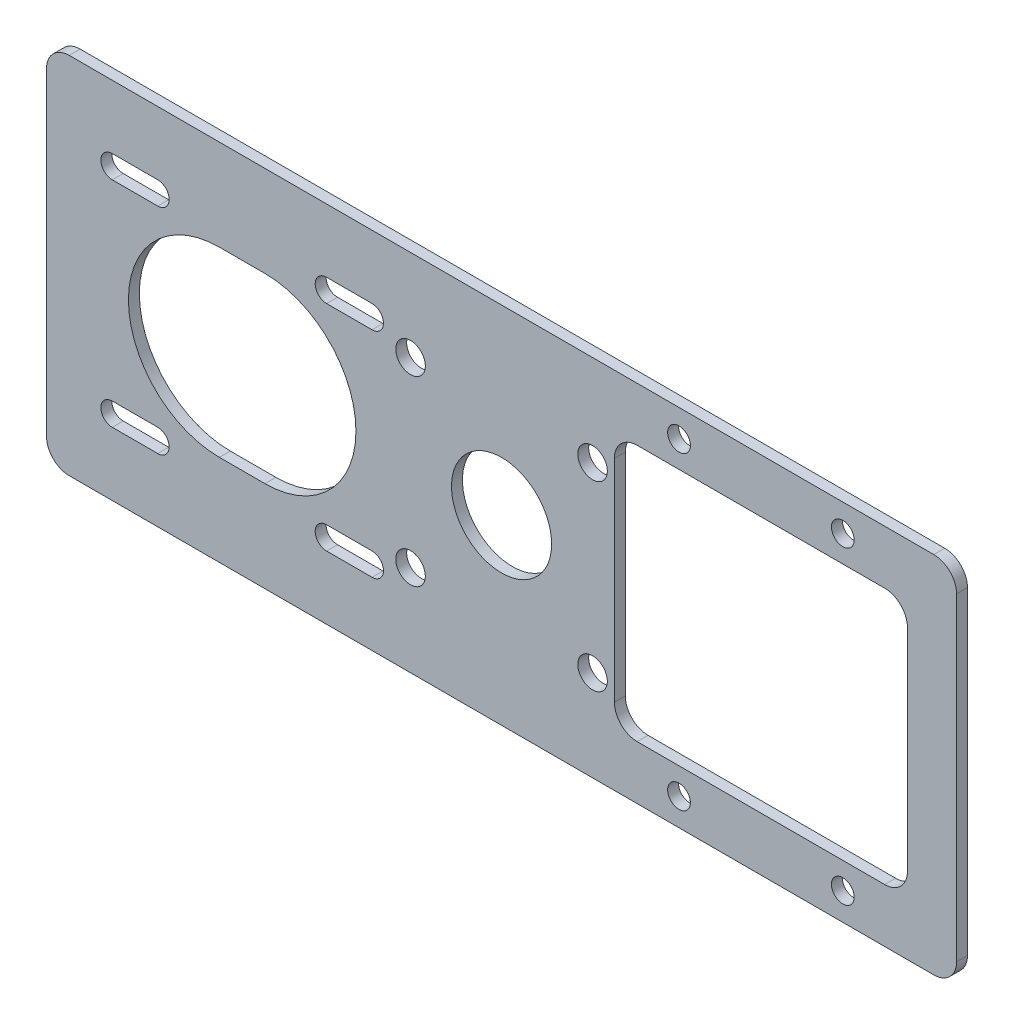
SolidWorks part; units mm, degrees
ref_plane "Alzado" through (0, 0, 0) normal (0, 0, 1) x (1, 0, 0)
ref_plane "Planta" through (0, 0, 0) normal (0, 1, 0) x (1, 0, 0)
ref_plane "Vista lateral" through (0, 0, 0) normal (1, 0, 0) x (0, 0, -1)
sketch "Croquis1" plane through (0, 0, 0) normal (0, 0, 1) x (1, 0, 0)
  line L1 (-100, 40) -> (100, 40)
  line L2 (-100, 40) -> (-100, -40)
  line L3 (-100, -40) -> (100, -40)
  line L4 (100, 40) -> (100, -40)
  line L5 (-100, 40) -> (100, -40) construction
  line L6 (-100, -40) -> (100, 40) construction
  point P0 (0, 0)
  dimension "D1" = 200
  dimension "D2" = 80
extrude "Saliente-Extruir1" add sketch "Croquis1" along normal blind 2.4
sketch "Croquis2" plane through (0, 0, 2.4) normal (0, 0, 1) x (1, 0, 0)
  circle A0 centre (0, 0) radius 11
  dimension "D1" = 22
extrude "Cortar-Extruir1" cut sketch "Croquis2" against normal through all
sketch "Croquis3" plane through (0, 0, 2.4) normal (0, 0, 1) x (1, 0, 0)
  line L0 (-20, 20) -> (-20, -20) construction
  line L1 (-27, 27) -> (27, 27) construction
  line L2 (-27, 27) -> (-27, -27) construction
  line L3 (-27, -27) -> (27, -27) construction
  line L4 (27, 27) -> (27, -27) construction
  line L5 (-27, 27) -> (27, -27) construction
  line L6 (-27, -27) -> (27, 27) construction
  line L7 (-20, -20) -> (20, -20) construction
  line L8 (20, 20) -> (20, -20) construction
  line L9 (-20, 20) -> (20, 20) construction
  circle A0 centre (20, 20) radius 3.25
  circle A1 centre (-20, 20) radius 3.25
  circle A2 centre (-20, -20) radius 3.25
  circle A3 centre (20, -20) radius 3.25
  point P0 (0, 0)
  dimension "D4" = 6.5
  dimension "D5" = 6.5
  dimension "D6" = 6.5
  dimension "D7" = 6.5
  dimension "D1" = 54
  dimension "D2" = 54
  dimension "D3" = 7
extrude "Cortar-Extruir2" cut sketch "Croquis3" against normal through all
sketch "Croquis4" plane through (0, 0, 2.4) normal (0, 0, 1) x (1, 0, 0)
  line L0 (0, 0) -> (-100, 0) construction
  line L1 (-100, 40) -> (-100, -40) construction
  line L2 (-57, 40) -> (-57, -40) construction
  line L3 (100, 40) -> (-100, 40) construction
  line L4 (-100, -40) -> (100, -40) construction
  line L5 (-62, 0) -> (-52, 0) construction
  line L6 (-85.2, 28.2) -> (-28.8, 28.2) construction
  line L7 (-85.2, 28.2) -> (-85.2, -28.2) construction
  line L8 (-85.2, -28.2) -> (-28.8, -28.2) construction
  line L9 (-28.8, 28.2) -> (-28.8, -28.2) construction
  line L10 (-85.2, 28.2) -> (-28.8, -28.2) construction
  line L11 (-85.2, -28.2) -> (-28.8, 28.2) construction
  line L12 (-27, 27) -> (27, 27) construction
  line L13 (-27, 27) -> (-27, -27) construction
  line L14 (-27, -27) -> (27, -27) construction
  line L15 (27, 27) -> (27, -27) construction
  line L16 (-27, 27) -> (27, -27) construction
  line L17 (-27, -27) -> (27, 27) construction
  line L18 (-62, 20) -> (-52, 20)
  line L19 (-62, -20) -> (-52, -20)
  line L20 (-85.55, 23.55) -> (-75.55, 23.55) construction
  line L21 (-33.45, -23.55) -> (-80.55, -23.55) construction
  line L22 (-33.45, -23.55) -> (-33.45, 23.55) construction
  line L23 (-33.45, 23.55) -> (-80.55, 23.55) construction
  line L24 (-80.55, -23.55) -> (-80.55, 23.55) construction
  line L25 (-33.45, -23.55) -> (-80.55, 23.55) construction
  line L26 (-33.45, 23.55) -> (-80.55, -23.55) construction
  line L27 (-85.55, 26.05) -> (-75.55, 26.05)
  line L28 (-85.55, 21.05) -> (-75.55, 21.05)
  line L29 (-28.45, 23.55) -> (-38.45, 23.55) construction
  line L30 (-28.45, 21.05) -> (-38.45, 21.05)
  line L31 (-28.45, 26.05) -> (-38.45, 26.05)
  line L32 (-28.45, -23.55) -> (-38.45, -23.55) construction
  line L33 (-28.45, -26.05) -> (-38.45, -26.05)
  line L34 (-28.45, -21.05) -> (-38.45, -21.05)
  line L35 (-85.55, -23.55) -> (-75.55, -23.55) construction
  line L36 (-85.55, -21.05) -> (-75.55, -21.05)
  line L37 (-85.55, -26.05) -> (-75.55, -26.05)
  arc A0 (-62, 20) -> (-62, -20) centre (-62, 0) ccw
  arc A1 (-52, -20) -> (-52, 20) centre (-52, 0) ccw
  arc A2 (-85.55, 26.05) -> (-85.55, 21.05) centre (-85.55, 23.55) ccw
  arc A3 (-75.55, 21.05) -> (-75.55, 26.05) centre (-75.55, 23.55) ccw
  arc A4 (-28.45, 21.05) -> (-28.45, 26.05) centre (-28.45, 23.55) ccw
  arc A5 (-38.45, 26.05) -> (-38.45, 21.05) centre (-38.45, 23.55) ccw
  arc A6 (-28.45, -26.05) -> (-28.45, -21.05) centre (-28.45, -23.55) ccw
  arc A7 (-38.45, -21.05) -> (-38.45, -26.05) centre (-38.45, -23.55) ccw
  arc A8 (-85.55, -21.05) -> (-85.55, -26.05) centre (-85.55, -23.55) ccw
  arc A9 (-75.55, -26.05) -> (-75.55, -21.05) centre (-75.55, -23.55) ccw
  point P11 (-57, 0)
  point P22 (-57, 0)
  point P27 (-57, 0)
  point P34 (-80.55, 23.55)
  point P40 (-33.45, 23.55)
  point P47 (-33.45, -23.55)
  point P54 (-80.55, -23.55)
  dimension "D7" = 20
  dimension "D10" = 2.5
  dimension "D11" = 2.5
  dimension "D12" = 2.5
  dimension "D13" = 2.5
  dimension "D1" = 56.4
  dimension "D2" = 56.4
  dimension "D3" = 57
  dimension "D4" = 54
  dimension "D5" = 54
  dimension "D6" = 10
  dimension "D8" = 47.1
  dimension "D9" = 47.1
  dimension "D14" = 10
  dimension "D15" = 10
  dimension "D16" = 10
  dimension "D17" = 10
extrude "Cortar-Extruir3" cut sketch "Croquis4" against normal blind 2.4
sketch "Croquis5" plane through (0, 0, 2.4) normal (0, 0, 1) x (1, 0, 0)
  line L0 (0, 0) -> (-100, 0) construction
  line L1 (-100, 40) -> (-100, -40) construction
  line L2 (-59.044, 5.7473) -> (-8.4442, 23.7431) construction
  line L3 (-59.044, -5.7473) -> (-8.4442, -23.7431) construction
  line L4 (0, 0) -> (100, 0) construction
  line L5 (100, -40) -> (100, 40) construction
  line L6 (59.044, 5.7473) -> (8.4442, 23.7431) construction
  line L7 (59.044, -5.7473) -> (8.4442, -23.7431) construction
  line L8 (-57, 40) -> (-57, -40) construction
  line L9 (100, 40) -> (-100, 40) construction
  line L10 (-100, -40) -> (100, -40) construction
  line L11 (57, 40) -> (57, -40) construction
  circle A0 centre (0, 0) radius 25.2 construction
  circle A1 centre (-57, 0) radius 6.1 construction
  circle A2 centre (57, 0) radius 6.1 construction
  dimension "D1" = 50.4
  dimension "D2" = 12.2
  dimension "D3" = 57
  dimension "D4" = 12.2
  dimension "D5" = 57
sketch "Croquis7" plane through (0, 0, 2.4) normal (0, 0, 1) x (1, 0, 0)
  line L1 (24.8, 28.2) -> (89.2, 28.2)
  line L2 (24.8, 28.2) -> (24.8, -28.2)
  line L3 (24.8, -28.2) -> (89.2, -28.2)
  line L4 (89.2, 28.2) -> (89.2, -28.2)
  line L5 (24.8, 28.2) -> (89.2, -28.2) construction
  line L6 (24.8, -28.2) -> (89.2, 28.2) construction
  point P0 (57, 0)
  dimension "D1" = 56.4
  dimension "D2" = 64.4
extrude "Cortar-Extruir4" cut sketch "Croquis7" against normal through all
sketch "Croquis8" plane through (0, 0, 2.4) normal (0, 0, 1) x (1, 0, 0)
  line L0 (100, 34) -> (-100, 34) construction
  line L1 (100, -40) -> (100, 40) construction
  line L2 (-100, 40) -> (-100, -40) construction
  line L3 (-100, -34) -> (100, -34) construction
  line L4 (39, 40) -> (39, -40) construction
  line L5 (100, 40) -> (-100, 40) construction
  line L6 (-100, -40) -> (100, -40) construction
  line L7 (75, 40) -> (75, -40) construction
  line L8 (0, 0) -> (100, 0) construction
  circle A0 centre (39, 34) radius 2.5
  circle A1 centre (75, 34) radius 2.5
  circle A2 centre (39, -34) radius 2.5
  circle A3 centre (75, -34) radius 2.5
  dimension "D5" = 5
  dimension "D6" = 5
  dimension "D7" = 5
  dimension "D8" = 5
  dimension "D1" = 18
  dimension "D2" = 18
  dimension "D3" = 34
  dimension "D4" = 34
extrude "Cortar-Extruir5" cut sketch "Croquis8" against normal through all
sketch "Croquis9" plane through (0, 0, 2.4) normal (0, 0, 1) x (1, 0, 0)
  line L0 (39, 40) -> (39, -40) construction
  line L1 (100, 40) -> (-100, 40) construction
  line L2 (-100, -40) -> (100, -40) construction
  line L3 (75, 40) -> (75, -40) construction
  line L4 (57, 40) -> (57, -40) construction
  line L5 (39, 34) -> (100, 34) construction
  line L6 (100, -40) -> (100, 40) construction
  line L7 (39, -34) -> (100, -34) construction
  line L9 (-33.45, -23.55) -> (-80.55, -23.55) construction
  line L10 (-33.45, -23.55) -> (-33.45, 23.55) construction
  line L11 (-33.45, 23.55) -> (-80.55, 23.55) construction
  line L12 (-80.55, -23.55) -> (-80.55, 23.55) construction
  line L13 (-33.45, -23.55) -> (-80.55, 23.55) construction
  line L14 (-33.45, 23.55) -> (-80.55, -23.55) construction
  point P24 (-57, 0)
  dimension "D1" = 18
  dimension "D2" = 18
  dimension "D3" = 47.1
  dimension "D4" = 47.1
fillet "Redondeo1" radius 5 4 edges at (89.2, -28.2, 1.2) (24.8, -28.2, 1.2) (89.2, 28.2, 1.2) (24.8, 28.2, 1.2)
fillet "Redondeo2" radius 5 4 edges at (100, -40, 1.2) (100, 40, 1.2) (-100, -40, 1.2) (-100, 40, 1.2)
